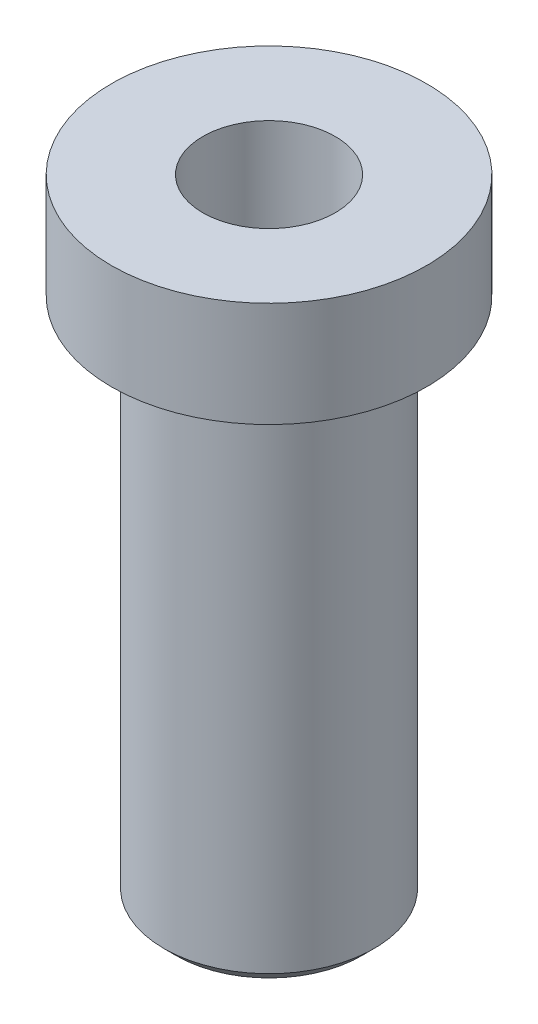
SolidWorks part; units mm, degrees
ref_plane "Front Plane" through (0, 0, 0) normal (0, 0, 1) x (1, 0, 0)
ref_plane "Top Plane" through (0, 0, 0) normal (0, 1, 0) x (1, 0, 0)
ref_plane "Right Plane" through (0, 0, 0) normal (1, 0, 0) x (0, 0, -1)
sketch "Sketch2" plane through (0, 0, 0) normal (0, 1, 0) x (1, 0, 0)
  circle A0 centre (0, 0) radius 12.7
  dimension "D1" = 25.4
extrude "Boss-Extrude1" add sketch "Sketch2" along normal mid plane 76.2
sketch "Sketch3" plane through (0, 38.1, 0) normal (0, 1, 0) x (1, 0, 0)
  circle A0 centre (0, 0) radius 19.05
  dimension "D1" = 38.1
extrude "Boss-Extrude2" add sketch "Sketch3" against normal blind 12.7
hole_wizard "Hole1" positions "Sketch4" profile "Sketch5" legacy end condition through all
sketch "Sketch4" plane through (0, 38.1, 0) normal (0, 1, 0) x (1, 0, 0)
  point P0 (0, 0)
sketch "Sketch5" plane through (0, 38.1, 0) normal (1, 0, 0) x (0, 0, 1)
  line L0 (0, 0) -> (0, 76.2)
  line L1 (0, 76.2) -> (8.001, 76.2)
  line L2 (8.001, 76.2) -> (8.001, 0)
  line L3 (8.001, 0) -> (0, 0)
  line L4 (0, 110) -> (0, -10) construction
  dimension "Diameter" = 16.002
  dimension "Depth" = 76.2
chamfer "Chamfer1" distance 1.524 angle 45 1 edges at (0, -38.1, 12.7)
